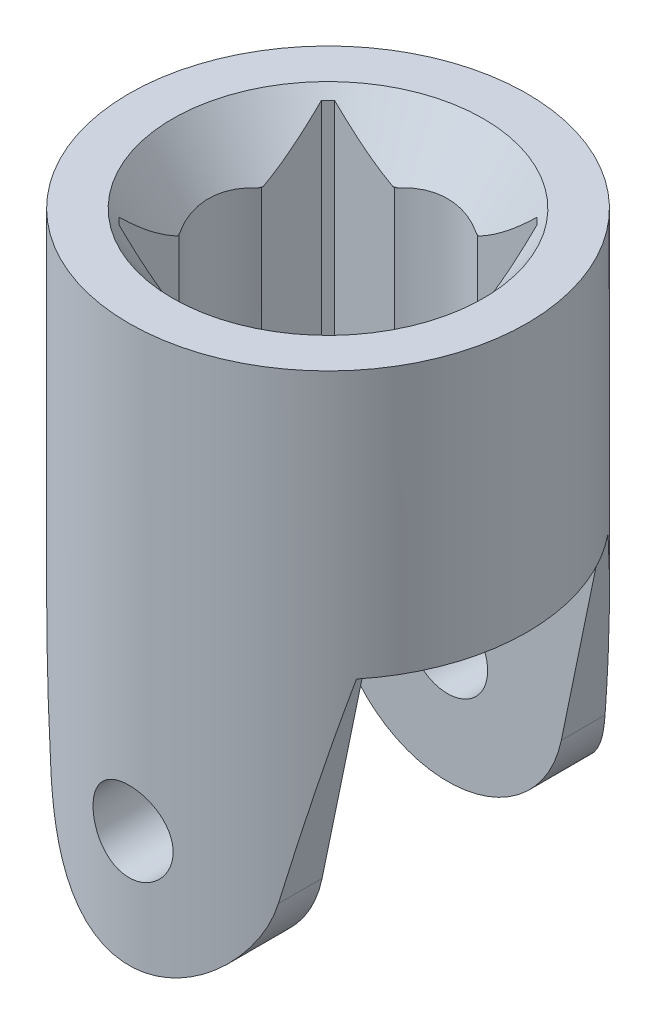
SolidWorks part; units mm, degrees
ref_plane "Front Plane" through (0, 0, 0) normal (0, 0, 1) x (1, 0, 0)
ref_plane "Top Plane" through (0, 0, 0) normal (0, 1, 0) x (1, 0, 0)
ref_plane "Right Plane" through (0, 0, 0) normal (1, 0, 0) x (0, 0, -1)
sketch "Sketch1" plane through (0, 0, 0) normal (0, 1, 0) x (1, 0, 0)
  circle A0 centre (0, 0) radius 12
  dimension "D1" = 24
extrude "Boss-Extrude1" add sketch "Sketch1" along normal blind 33.53
sketch "Sketch2" plane through (0, 33.53, 0) normal (0, 1, 0) x (1, 0, 0)
  line L0 (-6.5, 6.5) -> (-2.5, 6.5)
  line L1 (-6.5, 6.5) -> (6.5, 6.5) construction
  line L2 (-6.5, 6.5) -> (-6.5, -6.5) construction
  line L3 (-6.5, -6.5) -> (6.5, -6.5) construction
  line L4 (6.5, 6.5) -> (6.5, -6.5) construction
  line L5 (-6.5, 6.5) -> (6.5, -6.5) construction
  line L6 (-6.5, -6.5) -> (6.5, 6.5) construction
  line L7 (2.5, 6.5) -> (6.5, 6.5)
  line L8 (6.5, 6.5) -> (6.5, 2.5)
  line L9 (6.5, -2.5) -> (6.5, -6.5)
  line L10 (6.5, -6.5) -> (2.5, -6.5)
  line L11 (-2.5, -6.5) -> (-6.5, -6.5)
  line L12 (-6.5, -6.5) -> (-6.5, -2.5)
  line L13 (-6.5, 2.5) -> (-6.5, 6.5)
  arc A0 (-2.5, 6.5) -> (2.5, 6.5) centre (0, 2.4611) cw
  arc A1 (6.5, 2.5) -> (6.5, -2.5) centre (2.4611, 0) cw
  arc A2 (2.5, -6.5) -> (-2.5, -6.5) centre (0, -2.4611) cw
  arc A3 (-6.5, -2.5) -> (-6.5, 2.5) centre (-2.4611, 0) cw
  point P0 (0, 0)
  point P9 (0, 7.2111)
  point P28 (0, 0)
  dimension "D3" = 4.75
  dimension "D1" = 13
  dimension "D2" = 4
  dimension "D4" = 4
extrude "Cut-Extrude1" cut sketch "Sketch2" against normal blind 19.6
chamfer "Chamfer1" distance 0.4 angle 45 4 edges at (-6.5, 23.73, 6.5) (6.5, 23.73, 6.5) (-6.5, 23.73, -6.5) (6.5, 23.73, -6.5)
sketch "Sketch3" plane through (0, 33.53, 0) normal (0, 1, 0) x (1, 0, 0)
  circle A0 centre (0, 0) radius 9.375
  dimension "D1" = 18.75
extrude "Cut-Extrude2" cut sketch "Sketch3" against normal blind 3.4 draft 35
sketch "Sketch4" plane through (0, 0, 0) normal (0, -1, 0) x (1, 0, 0)
  line L1 (-12, 7.2111) -> (12, 7.2111)
  line L2 (-12, 7.2111) -> (-12, -7.2111)
  line L3 (-12, -7.2111) -> (12, -7.2111)
  line L4 (12, 7.2111) -> (12, -7.2111)
  arc A0 (2.5, 6.5) -> (-2.5, 6.5) centre (0, 2.4611) ccw construction
  arc A1 (-2.5, -6.5) -> (2.5, -6.5) centre (0, -2.4611) ccw construction
  circle A2 centre (0, 0) radius 12 construction
extrude "Cut-Extrude3" cut sketch "Sketch4" against normal blind 17.4
sketch "Sketch5" plane through (0, 0, 0) normal (0, 0, 1) x (1, 0, 0)
  line L0 (12, 17.4) -> (9.3, 17.4)
  line L1 (9.3, 17.4) -> (6.8548, 5.5817)
  line L2 (0, 0) -> (0, 33.53) construction
  line L3 (12, 33.53) -> (-12, 33.53) construction
  line L4 (-12, 17.4) -> (-9.3, 17.4)
  line L5 (-9.3, 17.4) -> (-6.8548, 5.5817)
  line L6 (-6.8548, 5.5817) -> (6.8548, 5.5817) construction
  line L7 (-12, 17.4) -> (-12, -3.1923)
  line L8 (-12, -3.1923) -> (12, -3.1923)
  line L9 (12, -3.1923) -> (12, 17.4)
  arc A0 (-6.8548, 5.5817) -> (6.8548, 5.5817) centre (0, 7) ccw
  circle A1 centre (0, 7) radius 2.415
  dimension "D1" = 7
  dimension "D3" = 4.83
  dimension "D2" = 2.7
extrude "Cut-Extrude4" cut sketch "Sketch5" against normal mid plane 67.4 contours A1 | A0 L5 L4 L7 L8 L9 L0 L1
